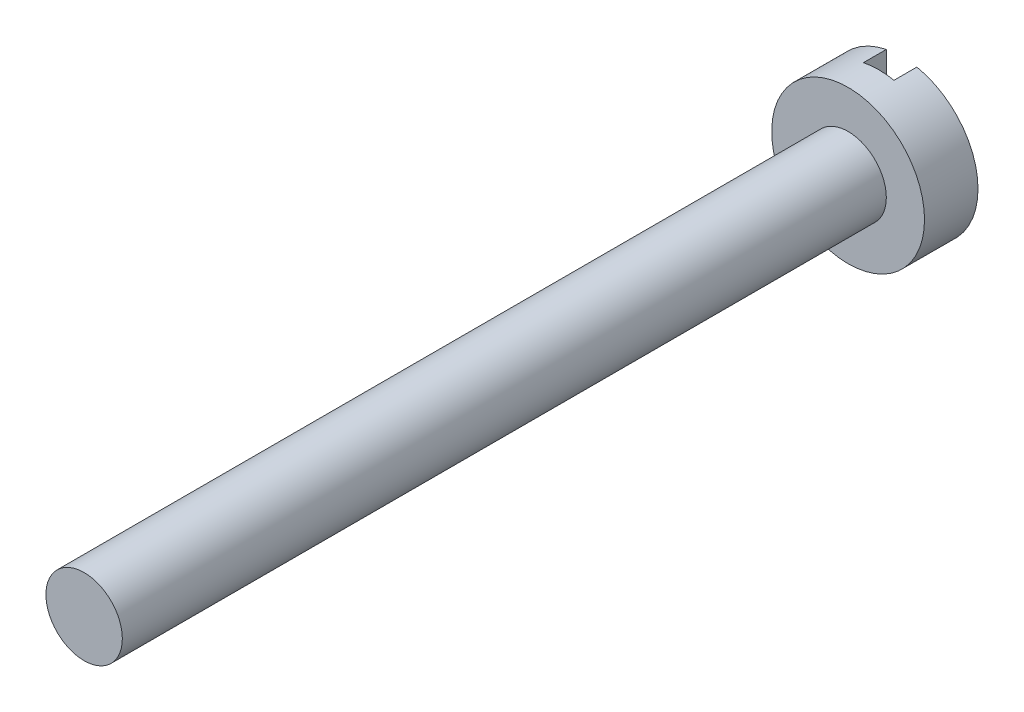
SolidWorks part; units mm, degrees
material "Plain Carbon Steel"
ref_plane "Front Plane" through (0, 0, 0) normal (0, 0, 1) x (1, 0, 0)
ref_plane "Top Plane" through (0, 0, 0) normal (0, 1, 0) x (1, 0, 0)
ref_plane "Right Plane" through (0, 0, 0) normal (1, 0, 0) x (0, 0, -1)
sketch "Sketch1" plane through (0, 0, 0) normal (0, 0, 1) x (1, 0, 0)
  circle A0 centre (0, 0) radius 1
  dimension "D1" = 2
extrude "Boss-Extrude1" add sketch "Sketch1" along normal blind 0.7
sketch "Sketch3" plane through (0, 0, 0.7) normal (0, 0, 1) x (1, 0, 0)
  circle A0 centre (0, 0) radius 0.5
  dimension "D1" = 1
extrude "Boss-Extrude2" add sketch "Sketch3" along normal blind 10
sketch "Sketch5" plane through (0, 0, 0) normal (0, 0, -1) x (-1, 0, 0)
  line L1 (-0.2, 1) -> (0.2, 1)
  line L2 (-0.2, 1) -> (-0.2, -1)
  line L3 (-0.2, -1) -> (0.2, -1)
  line L4 (0.2, 1) -> (0.2, -1)
  line L5 (-0.2, 1) -> (0.2, -1) construction
  line L6 (-0.2, -1) -> (0.2, 1) construction
  point P0 (0, 0)
  dimension "D1" = 0.4
  dimension "D2" = 2
extrude "Cut-Extrude1" cut sketch "Sketch5" against normal blind 0.3
